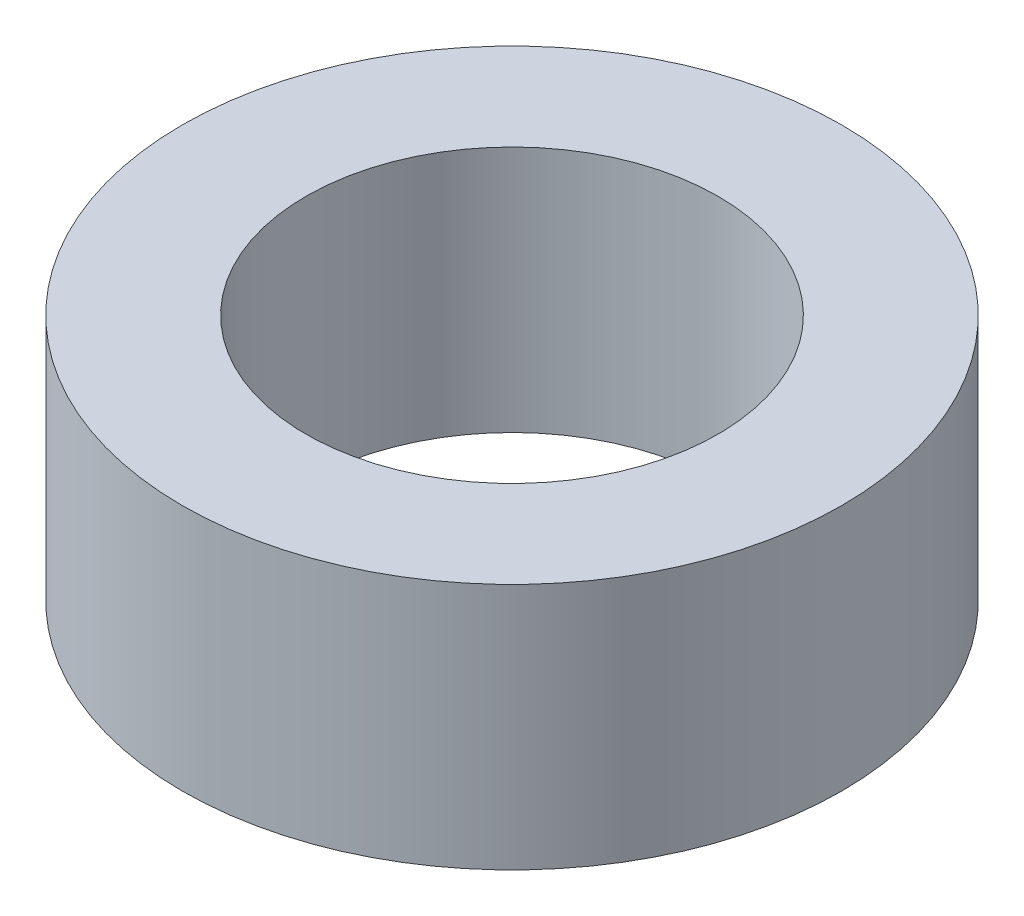
SolidWorks part; units mm, degrees
ref_plane "Front Plane" through (0, 0, 0) normal (0, 0, 1) x (1, 0, 0)
ref_plane "Top Plane" through (0, 0, 0) normal (0, 1, 0) x (1, 0, 0)
ref_plane "Right Plane" through (0, 0, 0) normal (1, 0, 0) x (0, 0, -1)
sketch "Sketch1" plane through (0, 0, 0) normal (0, 1, 0) x (1, 0, 0)
  circle A0 centre (0, 0) radius 12.7
  circle A1 centre (0, 0) radius 7.9375
  dimension "D1" = 15.875
  dimension "D2" = 25.4
extrude "Boss-Extrude1" add sketch "Sketch1" along normal blind 9.525
